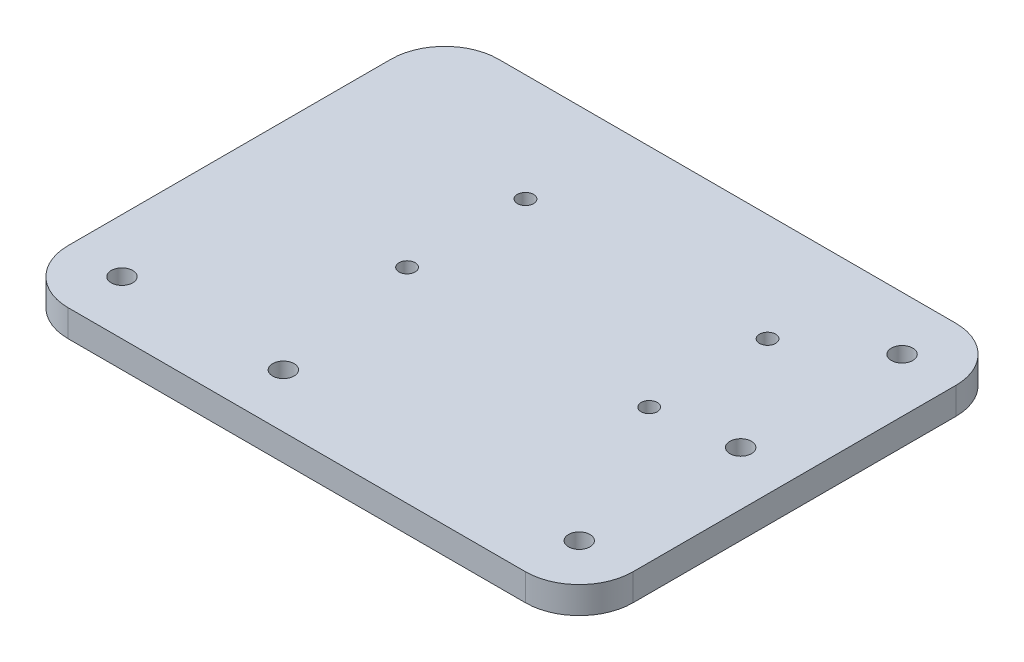
SolidWorks part; units mm, degrees
ref_plane "前视基准面" through (0, 0, 0) normal (0, 0, 1) x (1, 0, 0)
ref_plane "上视基准面" through (0, 0, 0) normal (0, 1, 0) x (1, 0, 0)
ref_plane "右视基准面" through (0, 0, 0) normal (1, 0, 0) x (0, 0, -1)
sketch "草图1" plane through (0, 0, 0) normal (0, 1, 0) x (1, 0, 0)
  line L1 (52.5, -40) -> (-52.5, -40)
  line L2 (52.5, -40) -> (52.5, 40)
  line L3 (52.5, 40) -> (-52.5, 40)
  line L4 (-52.5, -40) -> (-52.5, 40)
  line L5 (52.5, -40) -> (-52.5, 40) construction
  line L6 (52.5, 40) -> (-52.5, -40) construction
  point P0 (0, 0)
  dimension "D1" = 105
  dimension "D2" = 80
extrude "凸台-拉伸1" add sketch "草图1" along normal blind 5
sketch "草图2" plane through (0, 5, 0) normal (0, 1, 0) x (1, 0, 0)
  line L0 (-52.5, -40) -> (52.5, -40) construction
  circle A0 centre (-17.5, 20) radius 1.5
  circle A1 centre (27.5, 20) radius 1.5
  circle A2 centre (27.5, -2) radius 1.5
  circle A3 centre (-17.5, -2) radius 1.5
  dimension "D1" = 45
  dimension "D2" = 45
  dimension "D3" = 22
  dimension "D4" = 22
  dimension "D5" = 27.5
  dimension "D6" = 27.5
  dimension "D7" = 38
  dimension "D8" = 38
  dimension "D9" = 3
  dimension "D10" = 3
  dimension "D11" = 3
  dimension "D12" = 3
extrude "切除-拉伸1" cut sketch "草图2" against normal through all
sketch "草图3" plane through (0, 5, 0) normal (0, 1, 0) x (1, 0, 0)
  line L0 (-52.5, -40) -> (52.5, -40) construction
  line L1 (52.5, -40) -> (52.5, 40) construction
  circle A0 centre (-12.5, -30) radius 2
  circle A1 centre (-42.5, -30) radius 2
  circle A2 centre (42.5, 0) radius 2
  circle A3 centre (42.5, 30) radius 2
  circle A4 centre (42.5, -30) radius 2
  dimension "D1" = 10
  dimension "D2" = 10
  dimension "D3" = 10
  dimension "D4" = 10
  dimension "D5" = 4
  dimension "D6" = 4
  dimension "D7" = 4
  dimension "D8" = 4
  dimension "D9" = 30
  dimension "D10" = 30
  dimension "D11" = 40
  dimension "D12" = 65
  dimension "D13" = 4
  dimension "D14" = 10
  dimension "D15" = 10
extrude "切除-拉伸2" cut sketch "草图3" against normal blind 5
fillet "圆角1" radius 10 4 edges at (-52.5, 2.5, 40) (-52.5, 2.5, -40) (52.5, 2.5, -40) (52.5, 2.5, 40)
